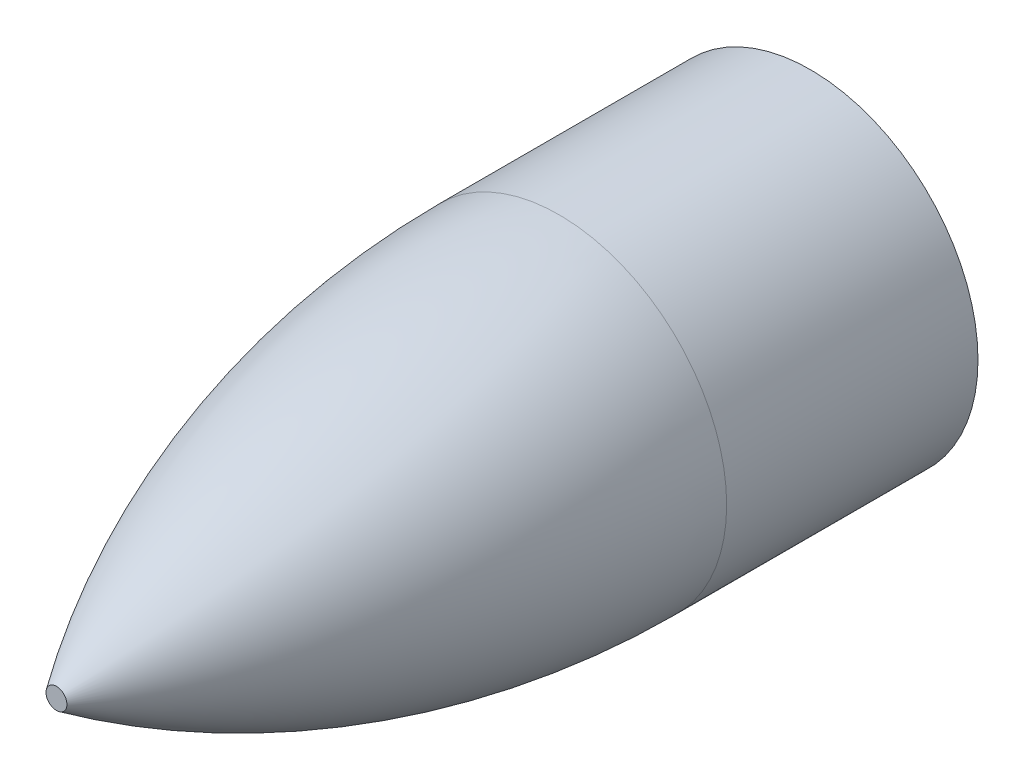
SolidWorks part; units mm, degrees
ref_plane "Front Plane" through (0, 0, 0) normal (0, 0, 1) x (1, 0, 0)
ref_plane "Top Plane" through (0, 0, 0) normal (0, 1, 0) x (1, 0, 0)
ref_plane "Right Plane" through (0, 0, 0) normal (1, 0, 0) x (0, 0, -1)
sketch "Sketch3" plane through (0, 0, 0) normal (1, 0, 0) x (0, 0, -1)
  line L0 (0, 0) -> (152.4, 0)
  line L1 (152.4, 0) -> (152.4, 3.175)
  line L2 (47.625, 0) -> (120.65, 0)
  line L3 (38.1, 12.7) -> (57.15, 12.7)
  line L5 (95.25, 10.3257) -> (152.4, 3.175)
  line L6 (0, 0) -> (0, 0.7937)
  line L7 (120.65, 0) -> (120.65, 3.9688)
  line L8 (120.65, 3.9688) -> (116.6813, 3.9687)
  line L9 (47.625, 9.525) -> (91.8932, 9.525)
  line L10 (120.65, 3.175) -> (122.2375, 3.175)
  line L11 (122.2375, 3.175) -> (125.5918, 6.5293)
  line L12 (57.15, 12.7) -> (57.15, 0)
  arc A1 (57.15, 12.7) -> (95.25, 10.3257) centre (57.15, -294.1784) cw
  arc A2 (0, 0.7937) -> (38.1, 12.7) centre (38.1, -54.2131) cw
  circle A3 centre (47.625, 0) radius 9.525
  arc A4 (91.8932, 9.525) -> (113.5348, 4.674) centre (91.8932, -41.1752) cw
  arc A5 (113.5348, 4.674) -> (116.6813, 3.9687) centre (116.6813, 11.3399) ccw
  dimension "D1" = 12.7
  dimension "D5" = 57.15
  dimension "D6" = 0.7937
  dimension "D8" = 73.025
  dimension "D9" = 19.05
  dimension "D2" = 38.1
  dimension "D3" = 3.175
  dimension "D4" = 19.05
  dimension "D7" = 152.4
  dimension "D10" = 3.9688
  dimension "D11" = 3.9688
  dimension "D12" = 31.75
  dimension "D13" = 1.5875
  dimension "D14" = 0.7937
  dimension "D15" = 135
revolve "Revolve2" add sketch "Sketch3" angle 360 about L0
sketch "Sketch4" plane through (0, 0, -57.15) normal (0, 0, -1) x (-1, 0, 0)
  circle A0 centre (0, 0) radius 11.2395
  dimension "D1" = 22.479
extrude "Cut-Extrude1" cut sketch "Sketch4" against normal blind 9.525
ref_plane "Plane1" through (0, 11.43, 0) normal (0, 1, 0) x (1, 0, 0)
sketch "Sketch5" plane through (0, 11.43, 0) normal (0, 1, 0) x (1, 0, 0)
  line L0 (12.7, 57.15) -> (-12.7, 57.15) construction
  line L1 (1.4605, 57.15) -> (-1.4605, 57.15)
  line L2 (1.4605, 57.15) -> (1.4605, 54.229)
  line L3 (1.4605, 54.229) -> (-1.4605, 54.229)
  line L4 (-1.4605, 57.15) -> (-1.4605, 54.229)
  line L5 (1.4605, 57.15) -> (-1.4605, 54.229) construction
  line L6 (1.4605, 54.229) -> (-1.4605, 57.15) construction
  line L7 (-12.7, 57.15) -> (12.7, 57.15) construction
  point P4 (0, 55.6895)
  point P7 (0, 0)
  point P12 (0, 0)
  point P13 (0, 0)
  point P14 (0, 57.15)
  dimension "D1" = 2.921
extrude "Boss-Extrude1" add sketch "Sketch5" against normal blind 1.8415
mirror "Mirror1" about plane through (0, 0, 0) normal (0, 1, 0) of "Boss-Extrude1"
